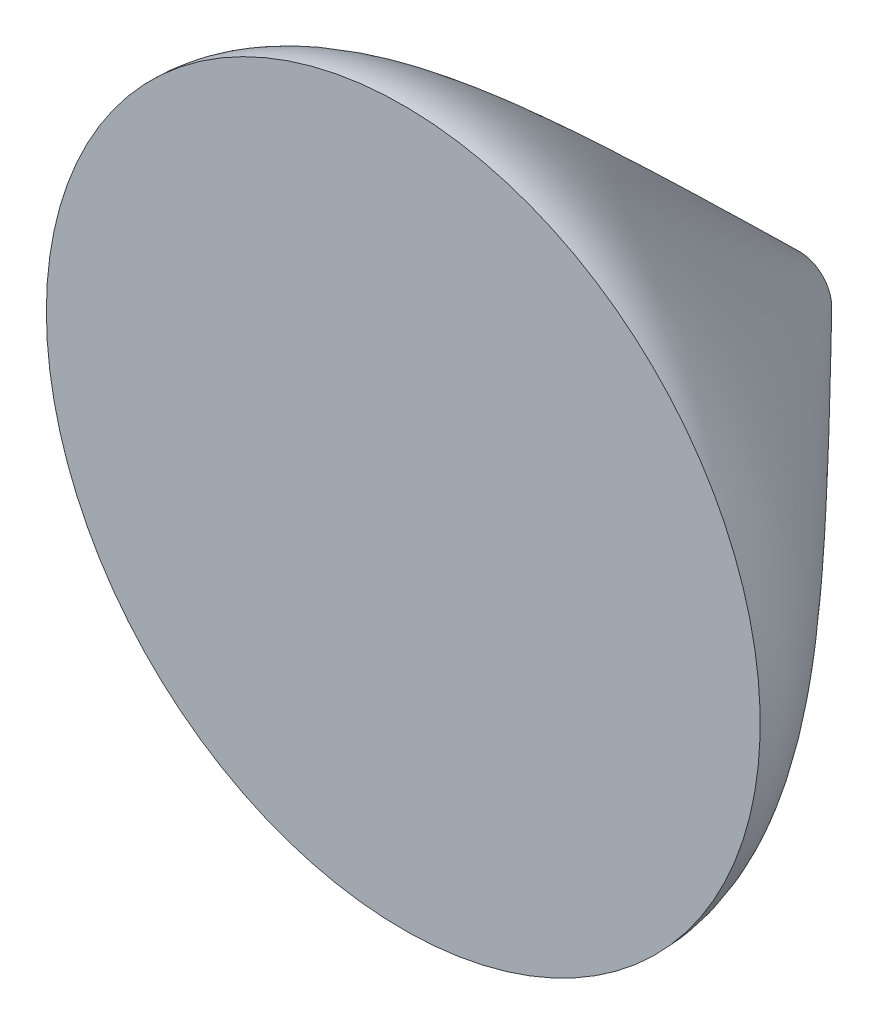
SolidWorks part; units mm, degrees
ref_plane "Front Plane" through (0, 0, 0) normal (0, 0, 1) x (1, 0, 0)
ref_plane "Top Plane" through (0, 0, 0) normal (0, 1, 0) x (1, 0, 0)
ref_plane "Right Plane" through (0, 0, 0) normal (1, 0, 0) x (0, 0, -1)
sketch "Sketch2" plane through (0, 0, 0) normal (0, 1, 0) x (1, 0, 0)
  line L0 (0, 2.5) -> (0, -2.5) construction
  line L2 (0, -2.5) -> (-4.5, -2.5)
  line L3 (0, -2.5) -> (0, 2.5)
  line L4 (0, 2.5) -> (-4.5, 2.5)
  line L5 (-4.5, -2.5) -> (-4.5, 2.5)
  dimension "D1" = 5
  dimension "D2" = 4.5
  dimension "D5" = 2.5
revolve "Revolve1" add sketch "Sketch2" angle 360 about L0
sketch "Sketch3" plane through (0, 0, 0) normal (0, 1, 0) x (1, 0, 0)
  line L0 (-4.5, -2.5) -> (-4.5, 7.4499)
  line L2 (4.5, -2.5) -> (-4.5, -2.5)
  line L3 (-4.5, 7.4499) -> (4.5, 7.4499)
  line L4 (0, -2.5) -> (0, 7.4499) construction
  line L5 (0, 2.5) -> (-0.401, 2.5)
  line L6 (4.5, 2.5) -> (-4.5, 2.5) construction
  line L7 (0, 2.5) -> (0, -2.5)
  line L8 (0, -2.5) -> (-4.5, -2.5)
  line L9 (-4.5, -2.5) -> (-4.5, 2.5)
  line L10 (-4.5, 2.5) -> (-0.401, 2.5)
  spline S0 degree 4 poles (-4.5, -2.5) (-4.5, -2.4748) (-4.4987, -2.4363) (-4.4942, -2.3832) (-4.4835, -2.3139) (-4.4705, -2.2519) (-4.4521, -2.1838) (-4.4271, -2.1083) (-4.3936, -2.0238) (-4.3481, -1.9253) (-4.2846, -1.8056) (-4.1899, -1.6492) (-4.0379, -1.4272) (-3.754, -1.0586) (-3.1392, -0.3457) (-2.1456, 0.7105) (-0.8258, 2.0711) (0.7574, 3.6788) (2.3589, 5.2962) (3.9912, 6.9389) (5.5804, 8.5357) (7.2429, 10.2037) (8.7876, 11.7528) (10.5275, 13.4963) (11.9456, 14.9171) (13.9818, 16.9562) (14.8901, 17.8656) (15.9485, 18.9252) (16.4065, 19.3837) knots 0 0 0 0 0 0.003317 0.005078 0.007018 0.009237 0.011659 0.014369 0.017486 0.021214 0.025938 0.032237 0.041524 0.056725 0.087085 0.156505 0.231998 0.307491 0.382984 0.458476 0.533969 0.609462 0.684955 0.760448 0.83594 0.911433 1 1 1 1 1 construction
  spline S1 degree 4 poles (-4.5, -2.5) (-4.5, -2.4748) (-4.4987, -2.4363) (-4.4942, -2.3832) (-4.4835, -2.3139) (-4.4705, -2.2519) (-4.4521, -2.1838) (-4.4271, -2.1083) (-4.3936, -2.0238) (-4.3481, -1.9253) (-4.2846, -1.8056) (-4.1899, -1.6492) (-4.0379, -1.4272) (-3.754, -1.0586) (-3.1392, -0.3457) (-2.1456, 0.7105) (-0.8258, 2.0711) (0.7574, 3.6788) (2.2874, 5.224) (3.4375, 6.3817) (4.1699, 7.118) (4.5, 7.4499) knots 0 0 0 0 0 0.003317 0.005078 0.007018 0.009237 0.011659 0.014369 0.017486 0.021214 0.025938 0.032237 0.041524 0.056725 0.087085 0.156505 0.231998 0.307491 0.382984 0.444998 0.444998 0.444998 0.444998 0.444998
  dimension "D1" = 0
  dimension "D2" = 0
revolve "Cut-Revolve5" cut sketch "Sketch3" angle 360 about L7
